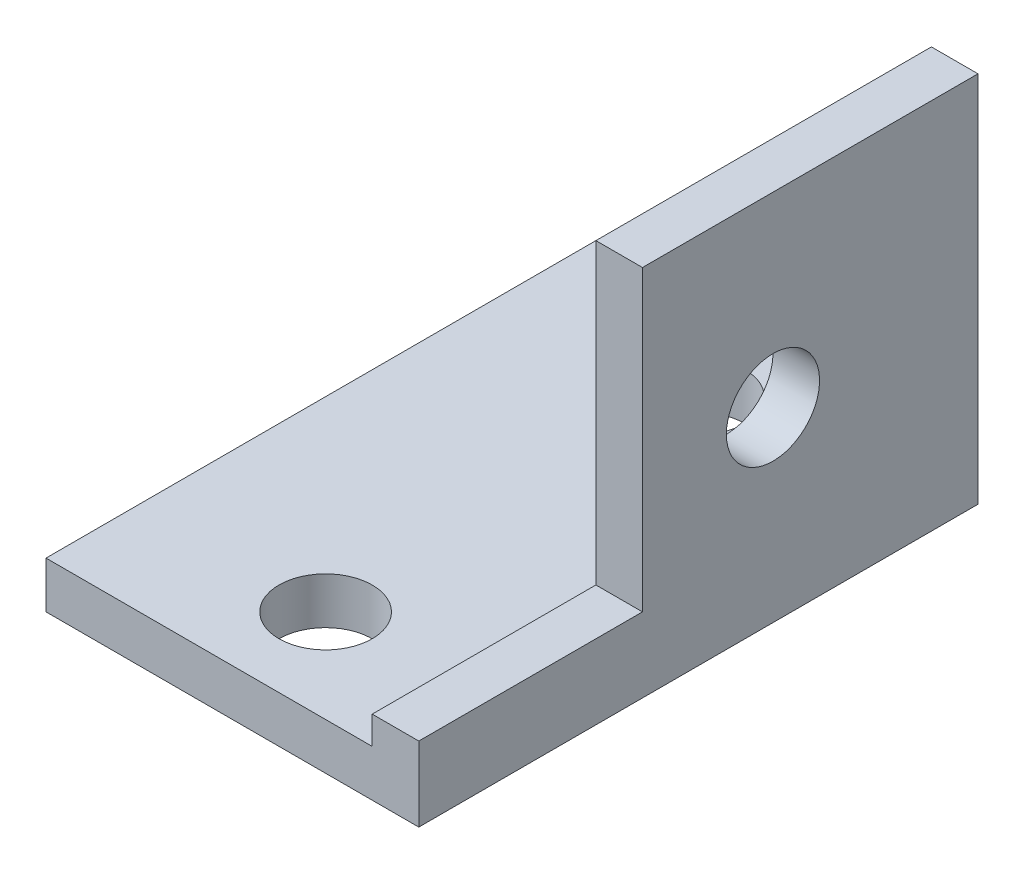
SolidWorks part; units mm, degrees
ref_plane "Front Plane" through (0, 0, 0) normal (0, 0, 1) x (1, 0, 0)
ref_plane "Top Plane" through (0, 0, 0) normal (0, 1, 0) x (1, 0, 0)
ref_plane "Right Plane" through (0, 0, 0) normal (1, 0, 0) x (0, 0, -1)
sketch "Sketch1" plane through (0, 0, 0) normal (0, 1, 0) x (1, 0, 0)
  line L1 (-11.1125, 19.05) -> (11.1125, 19.05)
  line L2 (-11.1125, 19.05) -> (-11.1125, -19.05)
  line L3 (-11.1125, -19.05) -> (11.1125, -19.05)
  line L4 (11.1125, 19.05) -> (11.1125, -19.05)
  line L5 (-11.1125, 19.05) -> (11.1125, -19.05) construction
  line L6 (-11.1125, -19.05) -> (11.1125, 19.05) construction
  circle A0 centre (1.5875, 12.7) radius 3.175
  circle A1 centre (1.5875, -12.7) radius 3.175
  point P0 (0, 0)
  dimension "D3" = 6.35
  dimension "D6" = 6.35
  dimension "D1" = 38.1
  dimension "D2" = 22.225
  dimension "D4" = 12.7
  dimension "D5" = 25.4
extrude "Boss-Extrude1" add sketch "Sketch1" along normal blind 3.175
sketch "Sketch2" plane through (0, 0, 0) normal (0, 1, 0) x (1, 0, 0)
  line L1 (11.1125, 19.05) -> (14.2875, 19.05)
  line L2 (11.1125, 19.05) -> (11.1125, -19.05)
  line L3 (11.1125, -19.05) -> (14.2875, -19.05)
  line L4 (14.2875, 19.05) -> (14.2875, -19.05)
  dimension "D1" = 3.175
extrude "Boss-Extrude2" add sketch "Sketch2" along normal blind 25.4
sketch "Sketch3" plane through (11.1125, 0, 0) normal (-1, 0, 0) x (0, 0, 1)
  line L0 (19.05, 25.4) -> (19.05, 3.175) construction
  line L1 (19.05, 25.4) -> (3.81, 25.4)
  line L2 (19.05, 25.4) -> (19.05, 5.08)
  line L3 (19.05, 5.08) -> (3.81, 5.08)
  line L4 (3.81, 25.4) -> (3.81, 5.08)
  line L5 (-19.05, 25.4) -> (19.05, 25.4) construction
  line L6 (-19.05, 25.4) -> (-19.05, 3.175) construction
  line L7 (19.05, 0) -> (-19.05, 0) construction
  line L8 (-19.05, 25.4) -> (-19.05, 0) construction
  circle A0 centre (-5.08, 12.7) radius 3.175
  dimension "D4" = 6.35
  dimension "D5" = 13.97
  dimension "D6" = 12.7
  dimension "D1" = 20.32
  dimension "D2" = 15.24
  dimension "D3" = 0
extrude "Cut-Extrude1" cut sketch "Sketch3" against normal through all
